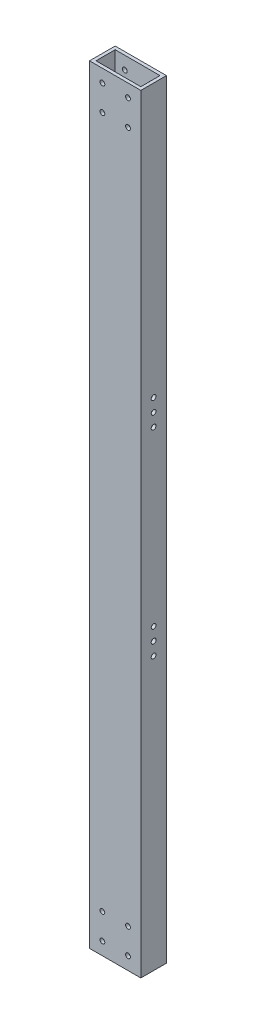
SolidWorks part; units mm, degrees
ref_plane "Front Plane" through (0, 0, 0) normal (0, 0, 1) x (1, 0, 0)
ref_plane "Top Plane" through (0, 0, 0) normal (0, 1, 0) x (1, 0, 0)
ref_plane "Right Plane" through (0, 0, 0) normal (1, 0, 0) x (0, 0, -1)
sketch "Sketch1" plane through (0, 0, 0) normal (0, 1, 0) x (1, 0, 0)
  line L1 (25.4, 12.7) -> (-25.4, 12.7)
  line L2 (25.4, 12.7) -> (25.4, -12.7)
  line L3 (25.4, -12.7) -> (-25.4, -12.7)
  line L4 (-25.4, 12.7) -> (-25.4, -12.7)
  line L5 (0, -12.7) -> (0, 12.7) construction
  line L6 (25.4, 0) -> (-25.4, 0) construction
  point P0 (0, 0)
  dimension "D1" = 50.8
  dimension "D2" = 25.4
extrude "Boss-Extrude1" add sketch "Sketch1" along normal mid plane 762
shell "Shell1" thickness 3.175
sketch "Sketch4" plane through (25.4, 0, 0) normal (1, 0, 0) x (0, 0, -1)
  line L0 (0, 0) -> (0, 50000) construction
  line L2 (0, 85.5345) -> (0, 110.9345) construction
  line L3 (0, 0) -> (50000, 0) construction
  line L4 (8.3008, 76.2) -> (-8.3008, 76.2) construction
  line L5 (8.3008, 76.2) -> (8.3008, 120.269) construction
  line L6 (8.3008, 120.269) -> (-8.3008, 120.269) construction
  line L7 (-8.3008, 76.2) -> (-8.3008, 120.269) construction
  line L8 (0, 120.269) -> (0, 76.2) construction
  line L9 (8.3008, 98.2345) -> (-8.3008, 98.2345) construction
  line L10 (8.3008, -98.2345) -> (-8.3008, -98.2345) construction
  line L11 (0, -120.269) -> (0, -76.2) construction
  line L12 (-8.3008, -76.2) -> (-8.3008, -120.269) construction
  line L13 (8.3008, -120.269) -> (-8.3008, -120.269) construction
  line L14 (8.3008, -76.2) -> (8.3008, -120.269) construction
  line L15 (8.3008, -76.2) -> (-8.3008, -76.2) construction
  line L16 (0, -85.5345) -> (0, -110.9345) construction
  circle A0 centre (0, 110.9345) radius 2.3812
  circle A1 centre (0, 98.2345) radius 2.3812
  circle A4 centre (0, 85.5345) radius 2.3812
  circle A5 centre (0, -85.5345) radius 2.3812
  circle A6 centre (0, -98.2345) radius 2.3812
  circle A7 centre (0, -110.9345) radius 2.3812
  point P15 (0, 98.2345)
  point P29 (0, -98.2345)
  dimension "D1" = 4.7625
  dimension "D2" = 12.7
  dimension "D3" = 44.069
  dimension "D4" = 76.2
extrude "Cut-Extrude1" cut sketch "Sketch4" against normal through all
sketch "Sketch5" plane through (0, 0, 12.7) normal (0, 0, 1) x (1, 0, 0)
  line L0 (-25.4, 381) -> (25.4, 381) construction
  line L1 (12.7, 368.3) -> (-12.7, 368.3) construction
  line L2 (12.7, 368.3) -> (12.7, 342.9) construction
  line L3 (12.7, 342.9) -> (-12.7, 342.9) construction
  line L4 (-12.7, 368.3) -> (-12.7, 342.9) construction
  line L5 (0, 342.9) -> (0, 368.3) construction
  line L6 (12.7, 355.6) -> (-12.7, 355.6) construction
  line L7 (0, 0) -> (50000, 0) construction
  line L8 (12.7, -355.6) -> (-12.7, -355.6) construction
  line L9 (0, -342.9) -> (0, -368.3) construction
  line L10 (-12.7, -368.3) -> (-12.7, -342.9) construction
  line L11 (12.7, -342.9) -> (-12.7, -342.9) construction
  line L12 (12.7, -368.3) -> (12.7, -342.9) construction
  line L13 (12.7, -368.3) -> (-12.7, -368.3) construction
  circle A0 centre (-12.7, 368.3) radius 2.3813
  circle A1 centre (12.7, 368.3) radius 2.3813
  circle A2 centre (12.7, 342.9) radius 2.3813
  circle A3 centre (-12.7, 342.9) radius 2.3813
  circle A4 centre (-12.7, -342.9) radius 2.3813
  circle A5 centre (12.7, -342.9) radius 2.3813
  circle A6 centre (12.7, -368.3) radius 2.3813
  circle A7 centre (-12.7, -368.3) radius 2.3813
  point P8 (0, 355.6)
  point P27 (0, -355.6)
  dimension "D1" = 4.7625
  dimension "D2" = 25.4
  dimension "D3" = 12.7
extrude "Cut-Extrude2" cut sketch "Sketch5" against normal through all both
